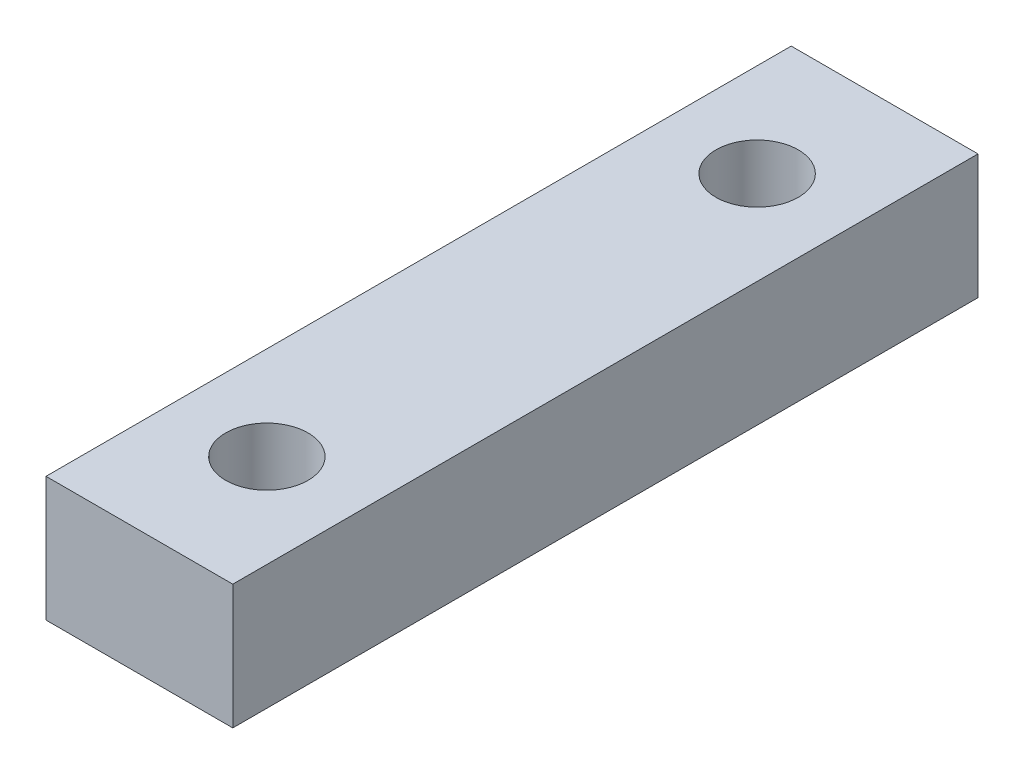
SolidWorks part; units mm, degrees
material "Low Carbon Steel"
ref_plane "Front Plane" through (0, 0, 0) normal (0, 0, 1) x (1, 0, 0)
ref_plane "Top Plane" through (0, 0, 0) normal (0, 1, 0) x (1, 0, 0)
ref_plane "Right Plane" through (0, 0, 0) normal (1, 0, 0) x (0, 0, -1)
sketch "Sketch1" plane through (0, 0, 0) normal (0, 0, 1) x (1, 0, 0)
  line L0 (-4.7625, -3.175) -> (4.7625, 3.175) construction
  line L1 (-4.7625, 3.175) -> (4.7625, 3.175)
  line L2 (-4.7625, 3.175) -> (-4.7625, -3.175)
  line L3 (-4.7625, -3.175) -> (4.7625, -3.175)
  line L4 (4.7625, 3.175) -> (4.7625, -3.175)
  dimension "D1" = 6.35
  dimension "D2" = 9.525
extrude "Boss-Extrude1" add sketch "Sketch1" along normal mid plane 38
hole_wizard "M5 Tapped Hole1" positions "Sketch3" profile "Sketch2" tap size "M5" standard "Peddi DIN" end condition through all
sketch "Sketch3" plane through (0, 3.175, 0) normal (0, 1, 0) x (1, 0, 0)
  line L0 (0, 12.5) -> (0, -12.5) construction
  point P0 (0, -12.5)
  point P1 (0, 12.5)
  dimension "D1" = 25
sketch "Sketch2" plane through (0, 3.175, 12.5) normal (1, 0, 0) x (0, 0, 1)
  line L0 (0, 0) -> (0, 6.35)
  line L1 (0, 6.35) -> (2.1, 6.35)
  line L2 (2.1, 6.35) -> (2.1, 0)
  line L5 (2.1, 0) -> (0, 0)
  line L11 (0, -6.35) -> (0, 107.95) construction
  dimension "Thru Tap Drill Dia." = 4.2
  dimension "Thru Tap Drill Depth" = 6.35
cosmetic thread "Hole Thread1"
cosmetic thread "Hole Thread2"
other "Freeze***"
